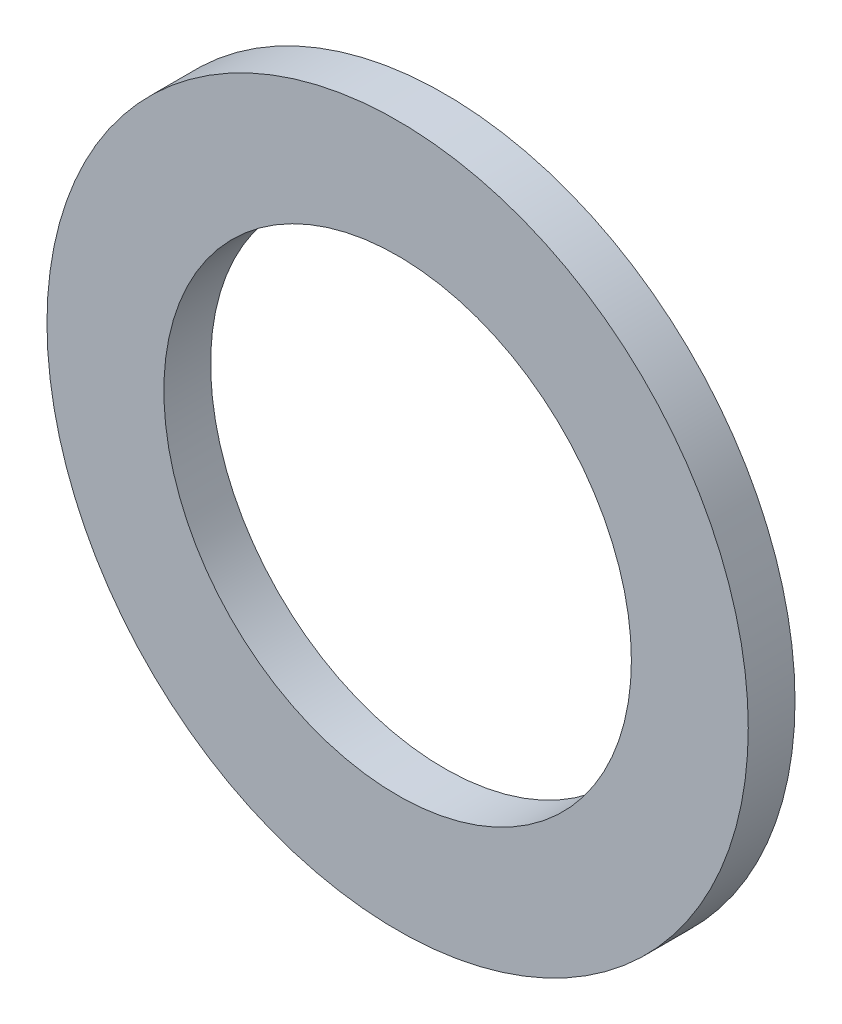
SolidWorks part; units mm, degrees
ref_plane "Plan1" through (0, 0, 0) normal (0, 0, 1) x (1, 0, 0)
ref_plane "Plan2" through (0, 0, 0) normal (0, 1, 0) x (1, 0, 0)
ref_plane "Plan3" through (0, 0, 0) normal (1, 0, 0) x (0, 0, -1)
sketch "Esquisse1" plane through (0, 0, 0) normal (0, 0, 1) x (1, 0, 0)
  circle A0 centre (0, 0) radius 10
  circle A1 centre (0, 0) radius 15
  dimension "D1" = 20
  dimension "D2" = 30
extrude "Base-Extrusion" add sketch "Esquisse1" along normal blind 2
